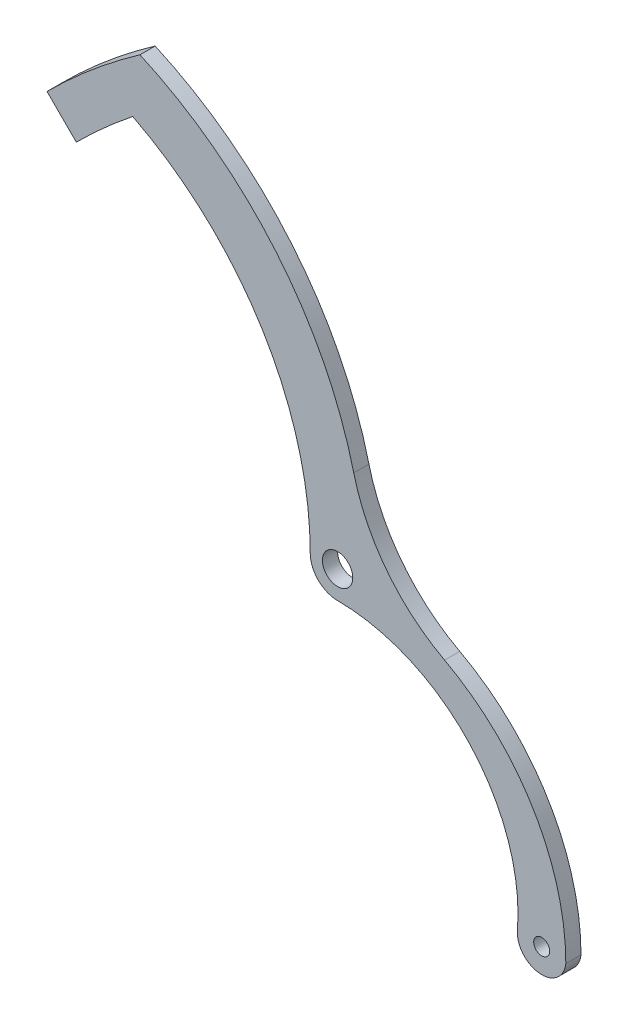
SolidWorks part; units mm, degrees
ref_plane "Front Plane" through (0, 0, 0) normal (0, 0, 1) x (1, 0, 0)
ref_plane "Top Plane" through (0, 0, 0) normal (0, 1, 0) x (1, 0, 0)
ref_plane "Right Plane" through (0, 0, 0) normal (1, 0, 0) x (0, 0, -1)
sketch "Sketch1" plane through (0, 0, 0) normal (0, 0, 1) x (1, 0, 0)
  line L0 (0, 0) -> (-67.195, 74.0597) construction
  line L1 (-67.195, 74.0597) -> (-154.5485, 170.3372) construction
  line L2 (0, 0) -> (-190.4184, 0) construction
  line L3 (-322.8491, -70) -> (261.6953, -70) construction
  line L4 (0, 0) -> (-292.0976, -90.5185) construction
  line L5 (-162.8722, 162.3966) -> (-153.22, 152.7726)
  circle A0 centre (0, 0) radius 8
  circle A1 centre (-100, 0) radius 70 construction
  circle A4 centre (0, 0) radius 230 construction
  circle A5 centre (0, 0) radius 2.6302
  circle A6 centre (0, 0) radius 100 construction
  circle A7 centre (-67.195, 74.0597) radius 9
  circle A8 centre (-67.195, 74.0597) radius 5
  circle A9 centre (-67.195, 74.0597) radius 11 construction
  circle A10 centre (-95.5187, -29.6004) radius 11 construction
  circle A11 centre (-95.5187, -29.6004) radius 9 construction
  arc A12 (-67.2306, 65.0597) -> (-7.9747, 0.6359) centre (-67.4664, 5.3797) cw
  arc A13 (-61.8714, 104.1421) -> (-132.2702, 188.1611) centre (-183.1104, 74.0597) ccw
  arc A14 (-162.8722, 162.3966) -> (-132.2702, 188.1611) centre (0, 0) cw
  arc A15 (-153.22, 152.7726) -> (-134.6541, 169.3638) centre (0, 0) cw
  arc A16 (-76.195, 74.0597) -> (-134.6541, 169.3638) centre (-183.1104, 74.0597) ccw
  arc A17 (-31.9625, 65.6983) -> (-61.8714, 104.1421) centre (-3.6372, 118.5914) cw
  arc A18 (-31.9625, 65.6983) -> (7.9512, -0.8819) centre (-67.6557, -0.9531) cw
  point P0 (-132.2702, 188.1611)
  point P32 (-58.195, 74.0597)
  point P37 (0, 0)
  point P38 (0, 0)
  point P39 (0, 0)
  dimension "D1" = 100
  dimension "D2" = 140
  dimension "D3" = 460
  dimension "D4" = 10
  dimension "D5" = 18
  dimension "D6" = 22
  dimension "D7" = 65
  dimension "D8" = 16
  dimension "D9" = 60
extrude "Boss-Extrude1" add sketch "Sketch1" along normal blind 5 contours A18 A0 A5 | A18 A7 A12 A0 | A7 A8 | A16 A7 A13 A14 L5 A15
